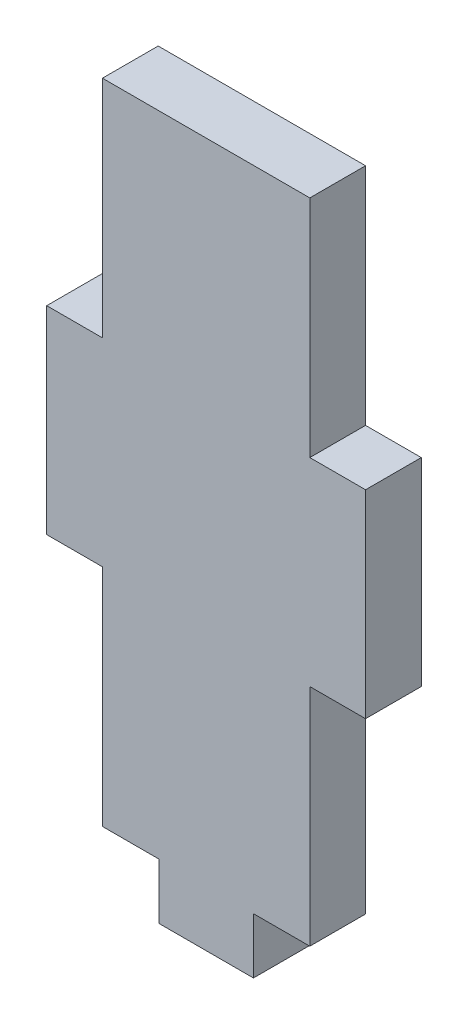
SolidWorks part; units mm, degrees
ref_plane "Front Plane" through (0, 0, 0) normal (0, 0, 1) x (1, 0, 0)
ref_plane "Top Plane" through (0, 0, 0) normal (0, 1, 0) x (1, 0, 0)
ref_plane "Right Plane" through (0, 0, 0) normal (1, 0, 0) x (0, 0, -1)
sketch "Sketch1" plane through (0, 0, 0) normal (0, 0, 1) x (1, 0, 0)
  line L0 (8, 7.65) -> (8, 25)
  line L1 (-8, -25) -> (-3.65, -25)
  line L2 (-8, -25) -> (-8, -7.65)
  line L3 (-8, 25) -> (8, 25)
  line L4 (8, -25) -> (8, -7.65)
  line L5 (-8, -25) -> (8, 25) construction
  line L6 (-8, 25) -> (8, -25) construction
  line L7 (8, -7.65) -> (12.3, -7.65)
  line L9 (8, 7.65) -> (12.3, 7.65)
  line L10 (12.3, -7.65) -> (12.3, 7.65)
  line L13 (0, 25) -> (0, -29.3) construction
  line L15 (-12.3, -7.65) -> (-12.3, 7.65)
  line L16 (-8, 7.65) -> (-12.3, 7.65)
  line L17 (-8, -7.65) -> (-12.3, -7.65)
  line L18 (-8, 7.65) -> (-8, 25)
  line L19 (3.65, -25) -> (8, -25)
  line L21 (-3.65, -25) -> (-3.65, -29.3)
  line L22 (-3.65, -29.3) -> (3.65, -29.3)
  line L23 (3.65, -25) -> (3.65, -29.3)
  point P0 (0, 0)
  point P13 (12.3, 0)
  point P22 (0, -29.3)
  dimension "D1" = 50
  dimension "D2" = 16
  dimension "D3" = 15.3
  dimension "D4" = 4.3
  dimension "D5" = 7.3
  dimension "D6" = 4.3
extrude "Boss-Extrude1" add sketch "Sketch1" along normal blind 4.3
